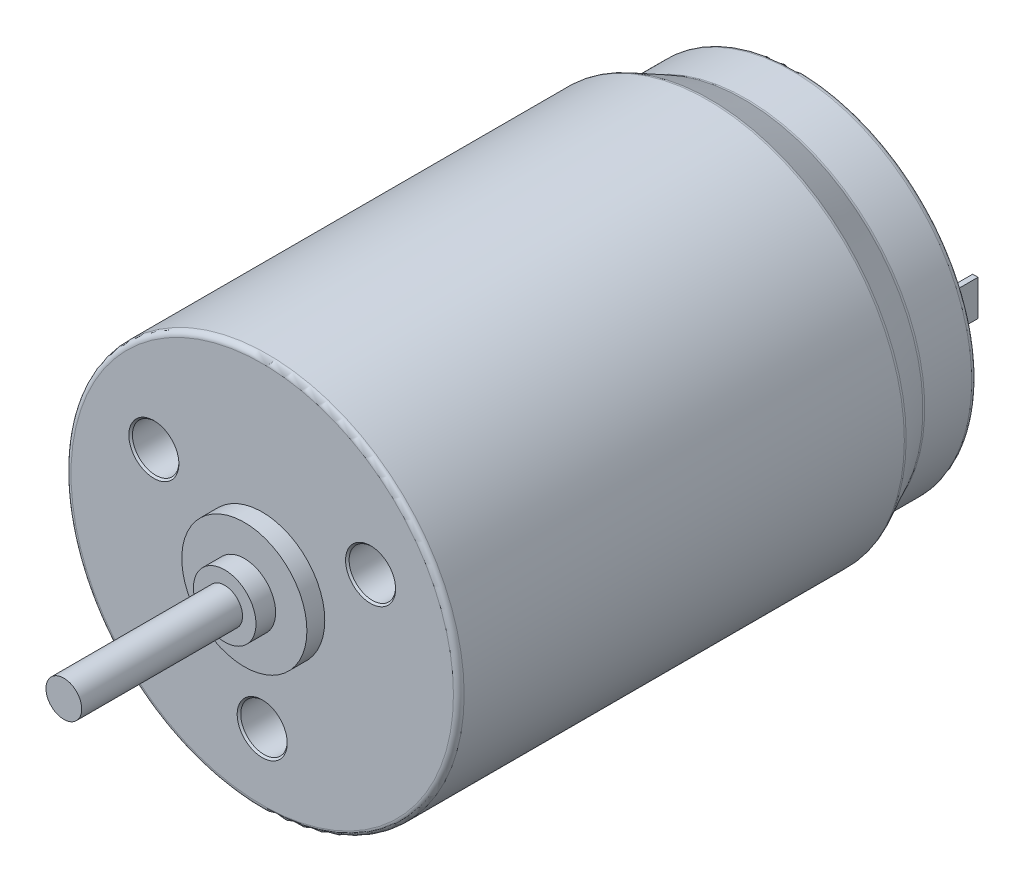
SolidWorks part; units mm, degrees
ref_plane "Front Plane" through (0, 0, 0) normal (0, 0, 1) x (1, 0, 0)
ref_plane "Top Plane" through (0, 0, 0) normal (0, 1, 0) x (1, 0, 0)
ref_plane "Right Plane" through (0, 0, 0) normal (1, 0, 0) x (0, 0, -1)
sketch "Sketch1" plane through (0, 0, 0) normal (0, 0, 1) x (1, 0, 0)
  circle A0 centre (0, 0) radius 11
  dimension "D1" = 22
extrude "Boss-Extrude1" add sketch "Sketch1" against normal blind 25
ref_plane "Plane1" through (0, 0, -27) normal (0, 0, -1) x (-1, 0, 0)
sketch "Sketch2" plane through (0, 0, -27) normal (0, 0, -1) x (-1, 0, 0)
  circle A0 centre (0, 0) radius 10
  dimension "D1" = 20
loft "Loft1" add profiles "Sketch2" section face at (11, 0, -25) section "Sketch2"
sketch "Sketch3" plane through (0, 0, -27) normal (0, 0, -1) x (-1, 0, 0)
  circle A1 centre (0, 0) radius 10
  circle A2 centre (0, 0) radius 10
  dimension "D1" = 0
extrude "Boss-Extrude2" add sketch "Sketch3" along normal blind 3
sketch "Sketch4" plane through (0, 0, 0) normal (0, 0, 1) x (1, 0, 0)
  circle A0 centre (0, 0) radius 7 construction
  circle A1 centre (-6.0622, 3.5) radius 1.3
  circle A2 centre (6.0622, 3.5) radius 1.3
  circle A3 centre (0, -7) radius 1.3
  point P9 (0, 0)
  dimension "D1" = 14
  dimension "D2" = 2.6
  dimension "D3" = 120
extrude "Cut-Extrude1" cut sketch "Sketch4" against normal blind 5
chamfer "Chamfer1" distance 0.1 3 edges at (1.3, -7, 0) (7.3622, 3.5, 0) (-4.7622, 3.5, 0)
sketch "Sketch5" plane through (0, 0, 0) normal (0, 0, 1) x (1, 0, 0)
  circle A0 centre (0, 0) radius 3.5
  dimension "D1" = 7
extrude "Boss-Extrude3" add sketch "Sketch5" along normal blind 1
sketch "Sketch6" plane through (0, 0, 1) normal (0, 0, 1) x (1, 0, 0)
  circle A0 centre (0, 0) radius 1.75
  dimension "D1" = 3.5
extrude "Boss-Extrude4" add sketch "Sketch6" along normal blind 1.1
sketch "Sketch7" plane through (0, 0, 2.1) normal (0, 0, 1) x (1, 0, 0)
  circle A0 centre (0, 0) radius 1
  dimension "D1" = 2
extrude "Boss-Extrude5" add sketch "Sketch7" along normal blind 9
sketch "Sketch8" plane through (0, 0, -30) normal (0, 0, -1) x (-1, 0, 0)
  line L0 (55, 0) -> (-55, 0) construction
  line L1 (-6.15, 1) -> (-5.85, 1)
  line L2 (-6.15, 1) -> (-6.15, -1)
  line L3 (-6.15, -1) -> (-5.85, -1)
  line L4 (-5.85, 1) -> (-5.85, -1)
  line L5 (-6.15, 1) -> (-5.85, -1) construction
  line L6 (-6.15, -1) -> (-5.85, 1) construction
  line L8 (5.85, 1) -> (6.15, 1)
  line L9 (5.85, 1) -> (5.85, -1)
  line L10 (5.85, -1) -> (6.15, -1)
  line L11 (6.15, 1) -> (6.15, -1)
  line L12 (5.85, 1) -> (6.15, -1) construction
  line L13 (5.85, -1) -> (6.15, 1) construction
  point P0 (-6, 0)
  point P7 (6, 0)
  dimension "D1" = 2
  dimension "D2" = 0.3
  dimension "D3" = 12
  dimension "D4" = 6
extrude "Boss-Extrude6" add sketch "Sketch8" along normal blind 3.9
fillet "Fillet1" radius 0.3 4 edges at (11, 0, 0) (-10, 0, -30) (-10, 0, -27) (11, 0, -25)
